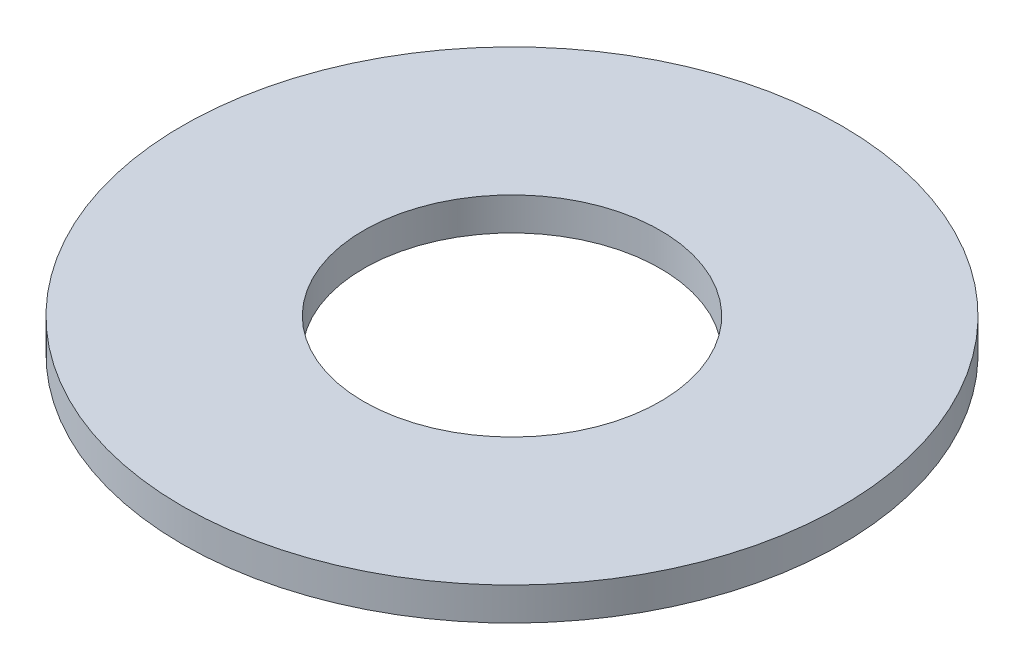
SolidWorks part; units mm, degrees
ref_plane "Front Plane" through (0, 0, 0) normal (0, 0, 1) x (1, 0, 0)
ref_plane "Top Plane" through (0, 0, 0) normal (0, 1, 0) x (1, 0, 0)
ref_plane "Right Plane" through (0, 0, 0) normal (1, 0, 0) x (0, 0, -1)
sketch "Sketch1" plane through (0, 0, 0) normal (0, 1, 0) x (1, 0, 0)
  circle A0 centre (0, 0) radius 2.25
  circle A1 centre (0, 0) radius 5
  dimension "D1" = 10
  dimension "D2" = 4.5
extrude "Boss-Extrude1" add sketch "Sketch1" along normal blind 0.5
